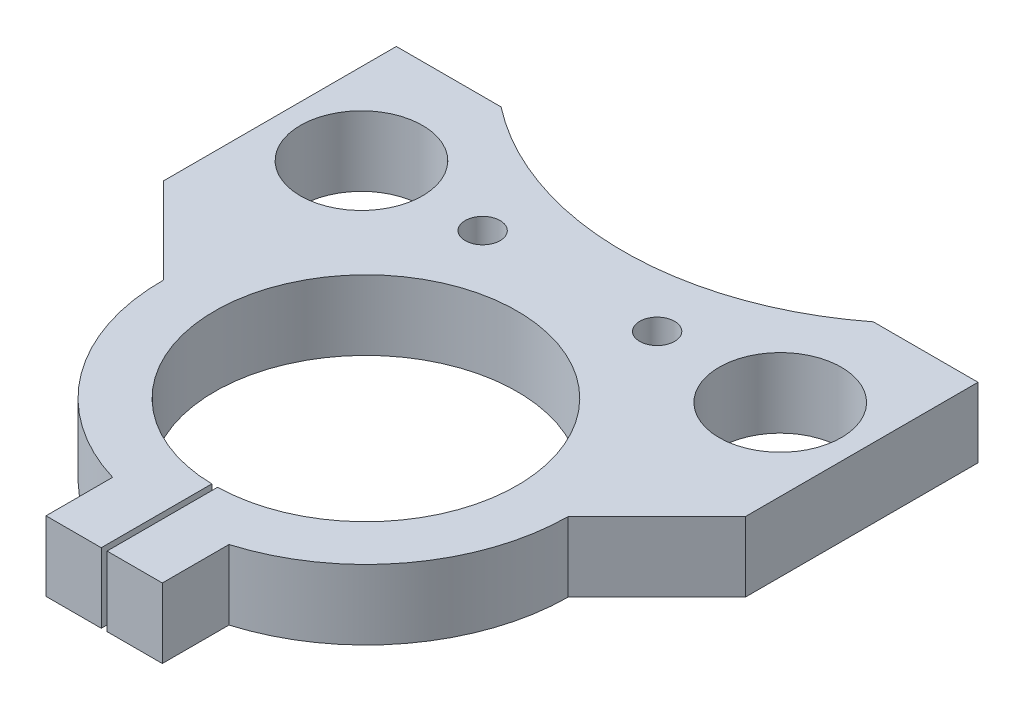
SolidWorks part; units mm, degrees
material "Beech"
ref_plane "Front Plane" through (0, 0, 0) normal (0, 0, 1) x (1, 0, 0)
ref_plane "Top Plane" through (0, 0, 0) normal (0, 1, 0) x (1, 0, 0)
ref_plane "Right Plane" through (0, 0, 0) normal (1, 0, 0) x (0, 0, -1)
sketch "Sketch1" plane through (0, 0, 0) normal (0, 1, 0) x (1, 0, 0)
  line L0 (-78.2213, 0) -> (76.4691, 0) construction
  line L1 (-50, 50) -> (50, 50)
  line L2 (-50, 50) -> (-50, -50)
  line L3 (-50, -50) -> (50, -50)
  line L4 (50, 50) -> (50, -50)
  line L5 (-50, 50) -> (50, -50) construction
  line L6 (-50, -50) -> (50, 50) construction
  line L7 (0, 33.1811) -> (0, -33.1904) construction
  circle A0 centre (0, 0) radius 11
  point P0 (0, 0)
  dimension "D2" = 22
  dimension "D1" = 100
  dimension "D7" = 100
extrude "Boss-Extrude1" add sketch "Sketch1" along normal blind 12
sketch "Sketch9" plane through (0, 12, 0) normal (0, 1, 0) x (1, 0, 0)
  line L0 (-50, -50) -> (-50, -100)
  line L1 (-50, -50) -> (50, -50)
  line L2 (50, -50) -> (50, -100)
  line L3 (50, -100) -> (-50, -100)
  dimension "D1" = 50
extrude "Boss-Extrude3" add sketch "Sketch9" against normal blind 12
sketch "Sketch4" plane through (0, 12, 0) normal (0, 1, 0) x (1, 0, 0)
  line L0 (-37.4627, -20) -> (37.4275, -20) construction
  circle A0 centre (-36, -20) radius 10.5
  circle A1 centre (36, -20) radius 10.5
  dimension "D2" = 21
  dimension "D3" = 21
  dimension "D4" = 36
  dimension "D5" = 72
  dimension "D1" = 20
extrude "Cut-Extrude3" cut sketch "Sketch4" against normal up to next
sketch "Sketch5" plane through (0, 12, 0) normal (0, 1, 0) x (1, 0, 0)
  line L0 (-50, 0) -> (-32, 0)
  line L1 (-50, 50) -> (-50, -100) construction
  line L2 (-32, 0) -> (-32, 18)
  line L3 (-32, 18) -> (32, 18)
  line L4 (32, 18) -> (32, 0)
  line L5 (32, 0) -> (50, 0)
  line L6 (50, -100) -> (50, 50) construction
  line L7 (50, 0) -> (50, 50)
  line L8 (50, 50) -> (-50, 50)
  line L9 (-50, 50) -> (-50, 0)
  dimension "D1" = 18
  dimension "D2" = 18
  dimension "D3" = 50
  dimension "D4" = 50
  dimension "D5" = 32
extrude "Cut-Extrude4" cut sketch "Sketch5" against normal up to next
sketch "Sketch6" plane through (0, 12, 0) normal (0, 1, 0) x (1, 0, 0)
  line L0 (0, -8.8019) -> (0, -112.6327) construction
  line L1 (-30.2744, -55) -> (29.8045, -55) construction
  circle A0 centre (-0.235, -55) radius 26
  circle A1 centre (-36, -20) radius 10.5 construction
  dimension "D1" = 52
  dimension "D2" = 35
extrude "Cut-Extrude5" cut sketch "Sketch6" against normal up to next
sketch "Sketch10" plane through (0, 12, 0) normal (0, 1, 0) x (1, 0, 0)
  line L0 (-0.235, -81) -> (-0.235, -100) construction
  line L1 (-10.235, -88.541) -> (-10.235, -100)
  line L2 (9.765, -88.541) -> (9.765, -100)
  line L3 (-10.235, -55) -> (-10.235, -122.2178) construction
  line L4 (9.765, -55) -> (9.765, -122.2178) construction
  line L5 (50, -40) -> (34.7642, -55.2358)
  line L6 (-50, 0) -> (-50, -100) construction
  line L7 (-50, -40) -> (-35.2342, -54.7658)
  line L8 (50, -100) -> (50, 0) construction
  line L9 (-50, -40) -> (-50, -100)
  line L10 (-50, -100) -> (-10.235, -100)
  line L11 (-50, -100) -> (50, -100) construction
  line L12 (9.765, -100) -> (50, -100)
  line L13 (50, -100) -> (50, -40)
  line L14 (-0.735, -80.9952) -> (-0.735, -100)
  line L15 (0.265, -80.9952) -> (0.265, -100)
  line L16 (0.265, -55) -> (0.265, -122.2178) construction
  line L17 (-0.235, -55) -> (-0.235, -122.2178) construction
  line L18 (-0.735, -55) -> (-0.735, -122.2178) construction
  line L19 (-0.735, -100) -> (0.265, -100)
  arc A0 (-35.2342, -54.7658) -> (-10.235, -88.541) centre (-0.235, -55) ccw
  circle A1 centre (-36, -20) radius 10.5 construction
  circle A2 centre (36, -20) radius 10.5 construction
  arc A3 (9.765, -88.541) -> (34.7642, -55.2358) centre (-0.235, -55) ccw
  circle A4 centre (-0.235, -55) radius 26 construction
  arc A5 (-0.735, -80.9952) -> (0.265, -80.9952) centre (-0.235, -55) ccw
  dimension "D1" = 70
  dimension "D4" = 20
  dimension "D5" = 20
  dimension "D8" = 45
  dimension "D9" = 45
  dimension "D2" = 10
  dimension "D3" = 10
  dimension "D6" = 0.5
  dimension "D7" = 0.5
extrude "Cut-Extrude6" cut sketch "Sketch10" against normal up to next
sketch "Sketch11" plane through (0, 12, 0) normal (0, 1, 0) x (1, 0, 0)
  circle A0 centre (0, 41.0455) radius 52.0455
extrude "Cut-Extrude7" cut sketch "Sketch11" against normal up to next
sketch "Sketch12" plane through (0, 12, 0) normal (0, 1, 0) x (1, 0, 0)
  line L0 (-36, -20) -> (36, -20) construction
  line L1 (-0.235, -29) -> (0, 0) construction
  arc A0 (0.265, -80.9952) -> (-0.735, -80.9952) centre (-0.235, -55) ccw construction
  circle A1 centre (-15.1625, -20) radius 3
  circle A2 centre (14.8375, -20) radius 3
  dimension "D1" = 6
  dimension "D2" = 6
  dimension "D3" = 30
  dimension "D4" = 15
extrude "Cut-Extrude8" cut sketch "Sketch12" against normal up to next
